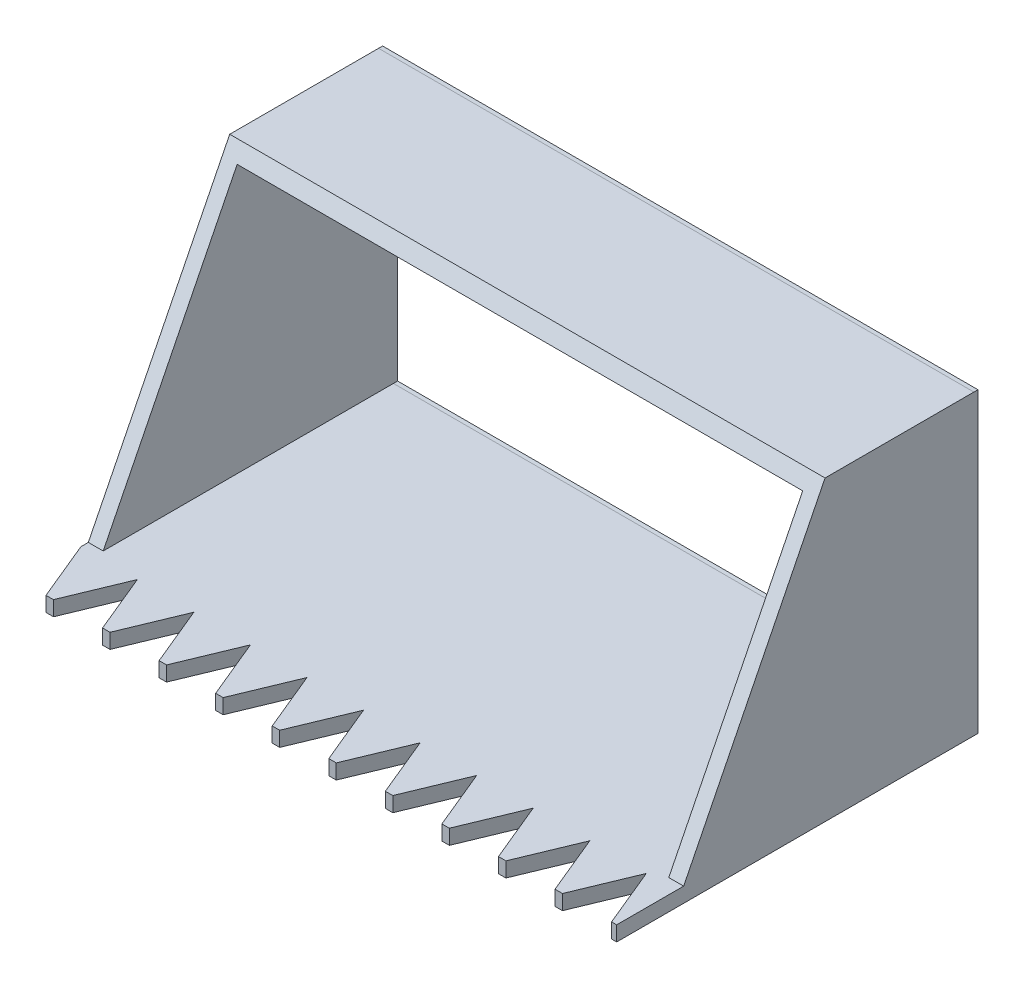
SolidWorks part; units mm, degrees
ref_plane "Front Plane" through (0, 0, 0) normal (0, 0, 1) x (1, 0, 0)
ref_plane "Top Plane" through (0, 0, 0) normal (0, 1, 0) x (1, 0, 0)
ref_plane "Right Plane" through (0, 0, 0) normal (1, 0, 0) x (0, 0, -1)
sketch "Sketch1" plane through (0, 0, 0) normal (0, 0, 1) x (1, 0, 0)
  line L0 (0, 0) -> (0, 50.8)
  line L1 (0, 50.8) -> (101.6, 50.8)
  line L2 (101.6, 50.8) -> (101.6, 0)
  line L3 (101.6, 0) -> (0, 0)
  dimension "D1" = 101.6
  dimension "D2" = 50.8
extrude "Boss-Extrude1" add sketch "Sketch1" against normal blind 50.8 contours L1 L2 L3 L0
sketch "Sketch2" plane through (0, 0, 0) normal (-1, 0, 0) x (0, 0, 1)
  line L0 (-50.8, 0) -> (-50.8, 50.8) construction
  line L1 (-50.8, 50.8) -> (-50.8, 0)
  arc A0 (-50.8, 50.8) -> (-50.8, 0) centre (-50.8, 25.4) ccw
extrude "Boss-Extrude2" add sketch "Sketch2" against normal up to surface (101.6 mm away) up to face at (101.6, 25.4, -25.4)
sketch "Sketch3" plane through (0, 0, 0) normal (-1, 0, 0) x (0, 0, 1)
  line L0 (0, 0) -> (-25.4, 50.8)
  line L1 (-50.8, 50.8) -> (0, 50.8) construction
  line L2 (-25.4, 50.8) -> (0, 50.8)
  line L3 (0, 50.8) -> (0, 0)
extrude "Cut-Extrude1" cut sketch "Sketch3" against normal up to surface (101.6 mm away) up to face at (101.6, 25.4, -31.75)
shell "Shell1" thickness 2.54
ref_plane "Plane1" through (0, 0, -2.54) normal (0, 0, 1) x (1, 0, 0)
sketch "Sketch4" plane through (0, 0, -2.54) normal (0, 0, 1) x (1, 0, 0)
  line L0 (0, 2.54) -> (101.6, 2.54)
  line L1 (0, 50.8) -> (0, 0) construction
  line L2 (101.6, 0) -> (101.6, 50.8) construction
  line L3 (101.6, 2.54) -> (101.6, 0)
  line L4 (101.6, 0) -> (0, 0) construction
  line L5 (101.6, 0) -> (0, 0)
  line L6 (0, 0) -> (0, 2.54)
  dimension "D1" = 2.54
extrude "Boss-Extrude3" add sketch "Sketch4" along normal blind 12.7
sketch "Sketch5" plane through (0, 2.54, 0) normal (0, 1, 0) x (1, 0, 0)
  line L0 (0, 0) -> (4.2084, -10.16)
  line L1 (5.4784, -10.16) -> (9.6868, 0)
  line L3 (4.2084, -10.16) -> (0, -10.16)
  line L4 (0, -10.16) -> (0, 0)
  line L8 (101.6, -10.16) -> (0, -10.16) construction
  line L9 (9.6868, 0) -> (9.6868, -10.16)
  line L10 (9.6868, -10.16) -> (5.4784, -10.16)
  dimension "D1" = 45
  dimension "D2" = 1.27
extrude "Cut-Extrude2" cut sketch "Sketch5" against normal up to surface (2.54 mm away) up to face at (50.8, 0, -20.32)
pattern_linear "LPattern1" count 11 spacing 9.652 along (1, 0, 0) of "Cut-Extrude2"
sketch "Sketch6" plane through (99.06, 0, 0) normal (-1, 0, 0) x (0, 0, 1)
  line L1 (-90.6732, 54.8068) -> (-51.5009, 54.8068)
  line L2 (-90.6732, 54.8068) -> (-90.6732, -9.5151)
  line L3 (-90.6732, -9.5151) -> (-51.5009, -9.5151)
  line L4 (-51.5009, 54.8068) -> (-51.5009, -9.5151)
extrude "Cut-Extrude3" cut sketch "Sketch6" against normal blind 5.08 and the other way blind 109.22
